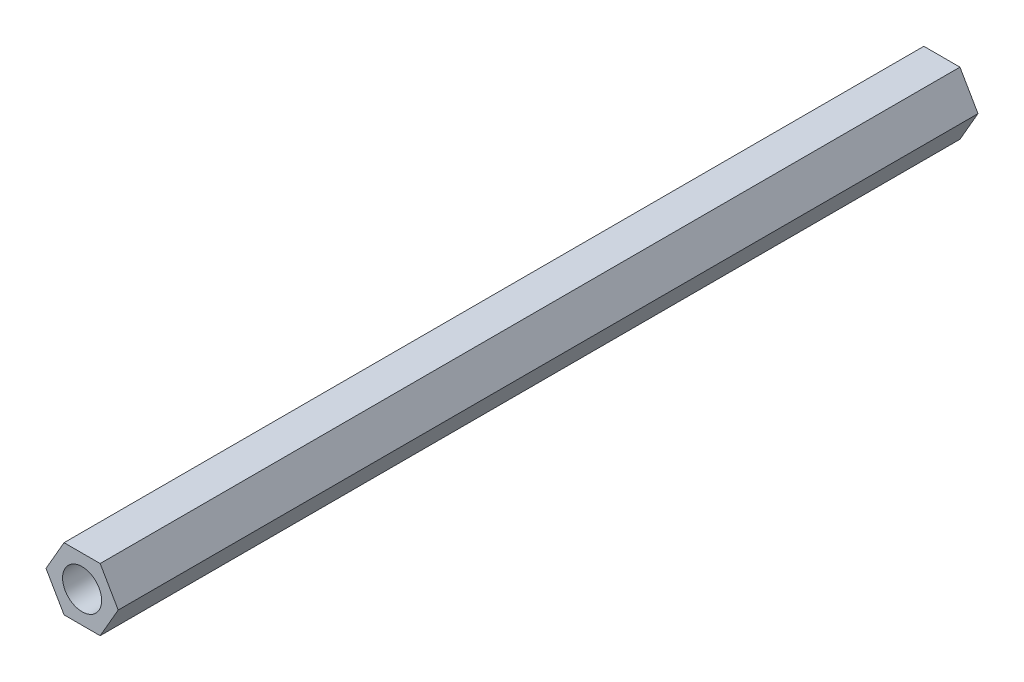
SolidWorks part; units mm, degrees
ref_plane "Front Plane" through (0, 0, 0) normal (0, 0, 1) x (1, 0, 0)
ref_plane "Top Plane" through (0, 0, 0) normal (0, 1, 0) x (1, 0, 0)
ref_plane "Right Plane" through (0, 0, 0) normal (1, 0, 0) x (0, 0, -1)
sketch "Sketch1" plane through (0, 0, 0) normal (0, 0, 1) x (1, 0, 0)
  line L1 (2.3094, 0) -> (1.1547, 2)
  line L2 (1.1547, 2) -> (-1.1547, 2)
  line L3 (-1.1547, 2) -> (-2.3094, 0)
  line L4 (-2.3094, 0) -> (-1.1547, -2)
  line L5 (-1.1547, -2) -> (1.1547, -2)
  line L6 (1.1547, -2) -> (2.3094, 0)
  circle A0 centre (0, 0) radius 2 construction
extrude "Boss-Extrude1" add sketch "Sketch1" against normal blind 55
sketch "Sketch2" plane through (0, 0, 0) normal (0, 0, 1) x (1, 0, 0)
  circle A0 centre (0, 0) radius 1.25
extrude "Cut-Extrude1" cut sketch "Sketch2" along normal through all and the other way through all
